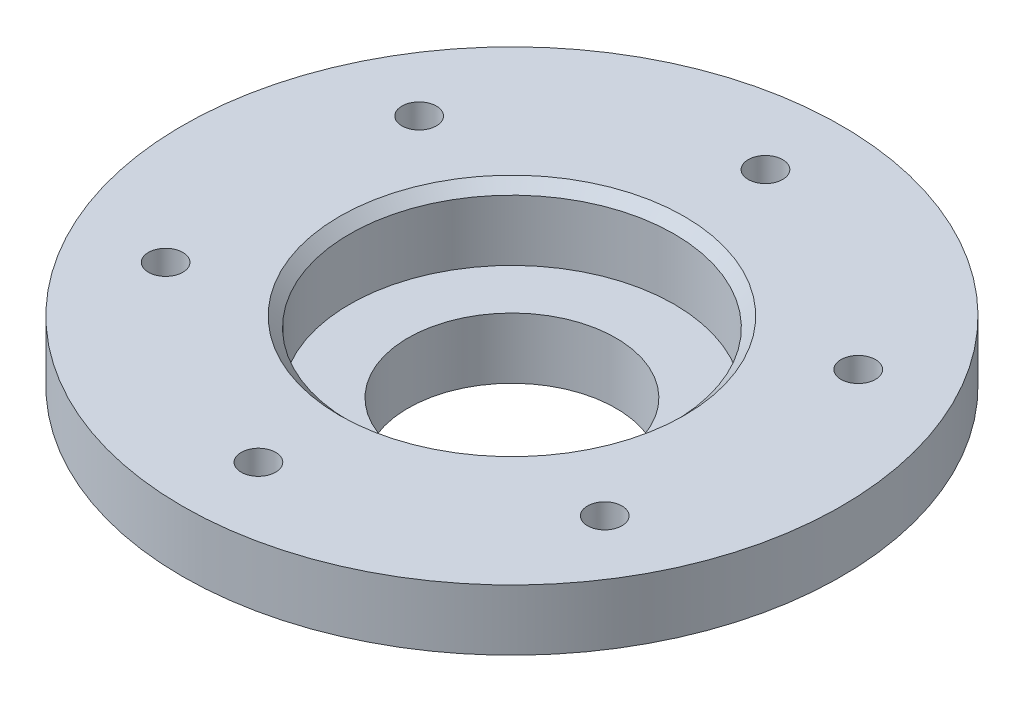
SolidWorks part; units mm, degrees
ref_plane "Ebene vorne" through (0, 0, 0) normal (0, 0, 1) x (1, 0, 0)
ref_plane "Ebene oben" through (0, 0, 0) normal (0, 1, 0) x (1, 0, 0)
ref_plane "Ebene rechts" through (0, 0, 0) normal (1, 0, 0) x (0, 0, -1)
sketch "Skizze1" plane through (0, 0, 0) normal (0, 0, 1) x (1, 0, 0)
  line L0 (0, 0) -> (0, -16486.4459) construction
  line L1 (10.25, 0) -> (20, 0)
  line L2 (20, 0) -> (20, 7)
  line L3 (20, 7) -> (32.5, 7)
  line L4 (32.5, 7) -> (32.5, 13)
  line L5 (32.5, 13) -> (16, 13)
  line L6 (16, 13) -> (16, 6)
  line L7 (16, 6) -> (10.25, 6)
  line L8 (10.25, 6) -> (10.25, 0)
  dimension "D1" = 40
  dimension "D2" = 65
  dimension "D3" = 13
  dimension "D4" = 20.5
  dimension "D5" = 32
  dimension "D6" = 7
  dimension "D7" = 7
revolve "Rotation1" add sketch "Skizze1" angle 360 about L0
chamfer "Fase1" distance 1 angle 45 1 edges at (0, 13, 16)
chamfer "Fase2" distance 1 angle 45 1 edges at (0, 0, 20)
hole_wizard "Formsenkung für M3 Senkschraube mit Schlitz/Kreuzschlitz1" positions "Skizze2" profile "Skizze3" countersink size "M3" standard "ISO" end condition through all
sketch "Skizze2" plane through (0, 7, 0) normal (0, -1, 0) x (-1, 0, 0)
  line L0 (0, 0) -> (0, -50000) construction
  point P5 (0, 25)
  dimension "D1" = 25
sketch "Skizze3" plane through (0, 7, -25) normal (1, 0, 0) x (0, 0, -1)
  line L0 (0, 0) -> (0, 6)
  line L1 (0, 6) -> (1.7, 6)
  line L2 (1.7, 6) -> (1.7, 1.45)
  line L3 (1.7, 1.45) -> (3.15, 0)
  line L5 (3.15, 0) -> (0, 0)
  line L6 (-1.7, 1.45) -> (-3.15, 0) construction
  line L11 (0, -6.35) -> (0, 107.95) construction
  dimension "Bohrerdurchmesser" = 3.4
  dimension "Bohrungstiefe" = 6
  dimension "Senkdurchmesser (Oben)" = 6.3
  dimension "Senkwinkel (Oben)" = 90
pattern_circular "Kreismuster1" count 6 over 360 about axis through (0, 0, 0) along (0, 1, 0) of "Formsenkung für M3 Senkschraube mit Schlitz/Kreuzschlitz1"
